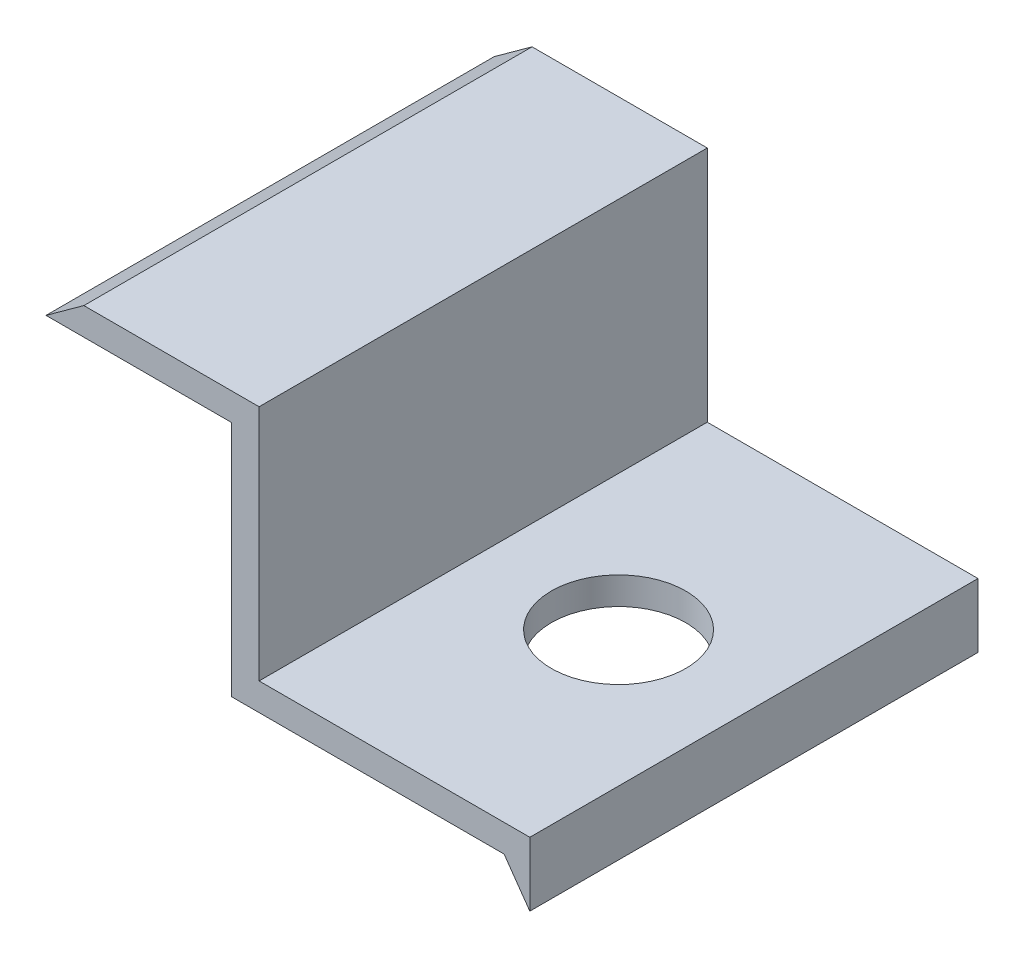
SolidWorks part; units mm, degrees
ref_plane "Front Plane" through (0, 0, 0) normal (0, 0, 1) x (1, 0, 0)
ref_plane "Top Plane" through (0, 0, 0) normal (0, 1, 0) x (1, 0, 0)
ref_plane "Right Plane" through (0, 0, 0) normal (1, 0, 0) x (0, 0, -1)
sketch "Sketch2" plane through (0, 0, 0) normal (0, 0, 1) x (1, 0, 0)
  line L0 (-33.2425, 19.1915) -> (-18.6445, 19.1915)
  line L1 (-18.6445, 19.1915) -> (-18.6445, -0.5931)
  line L2 (-18.6445, -0.5931) -> (3.9109, -0.5931)
  line L3 (3.9109, -0.5931) -> (3.9109, -5.9271)
  line L4 (3.9109, -5.9271) -> (1.7682, -2.8791)
  line L5 (1.7682, -2.8791) -> (-20.9305, -2.8791)
  line L6 (-20.9305, -2.8791) -> (-20.9305, 16.9055)
  line L7 (-20.9305, 16.9055) -> (-36.3977, 16.9055)
  line L8 (-36.3977, 16.9055) -> (-33.2425, 19.1915)
  dimension "D1" = 2.286
  dimension "D2" = 2.286
  dimension "D3" = 2.286
extrude "Boss-Extrude1" add sketch "Sketch2" against normal blind 37.338
sketch "Sketch3" plane through (0, -0.5931, 0) normal (0, 1, 0) x (1, 0, 0)
  line L0 (-7.3668, 37.338) -> (-7.3668, 0) construction
  line L1 (-18.6445, 18.669) -> (3.9109, 18.669) construction
  circle A0 centre (-7.3668, 18.669) radius 5.597
extrude "Cut-Extrude1" cut sketch "Sketch3" against normal blind 37.338
